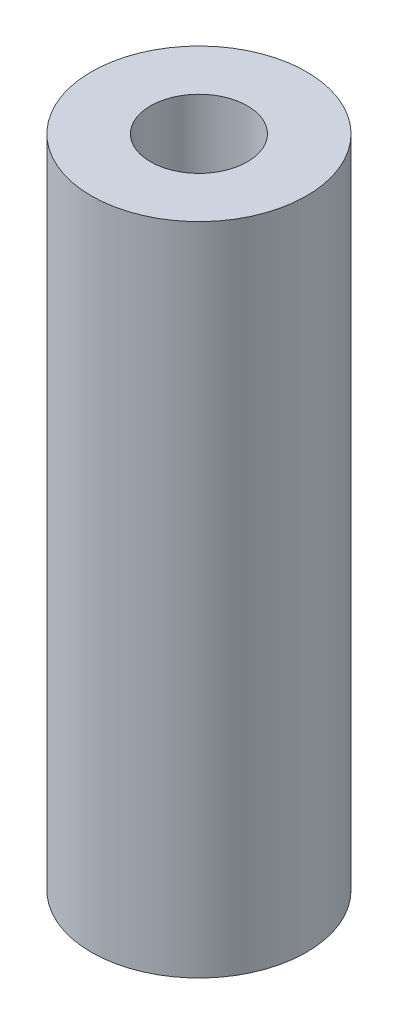
SolidWorks part; units mm, degrees
material "1060 Alloy"
ref_plane "Front Plane" through (0, 0, 0) normal (0, 0, 1) x (1, 0, 0)
ref_plane "Top Plane" through (0, 0, 0) normal (0, 1, 0) x (1, 0, 0)
ref_plane "Right Plane" through (0, 0, 0) normal (1, 0, 0) x (0, 0, -1)
sketch "Sketch1" plane through (0, 0, 0) normal (0, 1, 0) x (1, 0, 0)
  circle A0 centre (0, 0) radius 3
  dimension "D1" = 6
extrude "Boss-Extrude1" add sketch "Sketch1" along normal blind 18.27
hole_wizard "#6-32 Tapped Hole1" positions "Sketch3" profile "Sketch4" tap size "#6-32" standard "ANSI Inch"
sketch "Sketch3" plane through (0, 18.27, 0) normal (0, 1, 0) x (1, 0, 0)
  point P0 (0, 0)
sketch "Sketch4" plane through (0, 18.27, 0) normal (1, 0, 0) x (0, 0, 1)
  line L0 (0, 0) -> (0, 10.8127)
  line L1 (0, 10.8127) -> (1.3525, 10)
  line L2 (1.3525, 10) -> (1.3525, 0)
  line L5 (1.3525, 0) -> (0, 0)
  line L10 (0, 10.8127) -> (-1.3526, 10) construction
  line L11 (0, -6.35) -> (0, 107.95) construction
  dimension "Tap Drill Dia." = 2.7051
  dimension "Tap Drill Depth" = 10
  dimension "Drill Angle" = 118
cosmetic thread "Hole Thread1" parameters "D1"=7.01, "D2"=3.5052
hole_wizard "#6-32 Tapped Hole2" positions "Sketch5" profile "Sketch6" tap size "#6-32" standard "ANSI Inch"
sketch "Sketch5" plane through (0, 0, 0) normal (0, -1, 0) x (-1, 0, 0)
  point P0 (0, 0)
sketch "Sketch6" plane through (0, 0, 0) normal (1, 0, 0) x (0, 0, -1)
  line L0 (0, 0) -> (0, 10.8127)
  line L1 (0, 10.8127) -> (1.3525, 10)
  line L2 (1.3525, 10) -> (1.3525, 0)
  line L5 (1.3525, 0) -> (0, 0)
  line L10 (0, 10.8127) -> (-1.3525, 10) construction
  line L11 (0, -6.35) -> (0, 107.95) construction
  dimension "Tap Drill Dia." = 2.7051
  dimension "Tap Drill Depth" = 10
  dimension "Drill Angle" = 118
cosmetic thread "Hole Thread2" parameters "D1"=7.01, "D2"=3.5052
